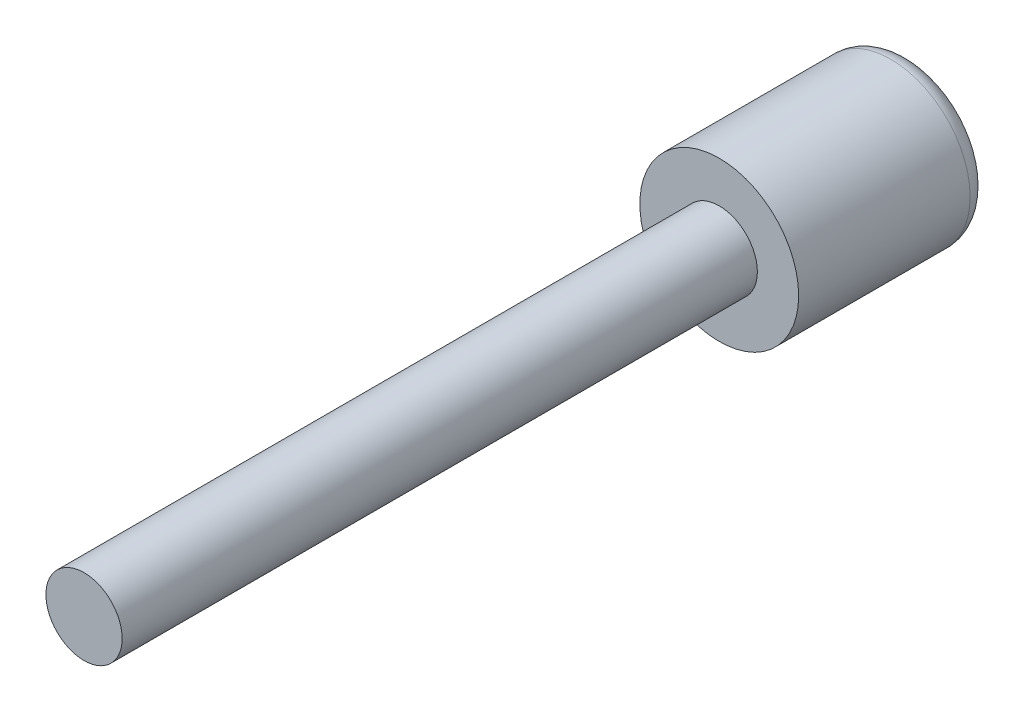
SolidWorks part; units mm, degrees
ref_plane "Front Plane" through (0, 0, 0) normal (0, 0, 1) x (1, 0, 0)
ref_plane "Top Plane" through (0, 0, 0) normal (0, 1, 0) x (1, 0, 0)
ref_plane "Right Plane" through (0, 0, 0) normal (1, 0, 0) x (0, 0, -1)
sketch "Sketch1" plane through (0, 0, 0) normal (0, 0, 1) x (1, 0, 0)
  circle A0 centre (0, 0) radius 1.25
  dimension "D1" = 2.5
extrude "Boss-Extrude1" add sketch "Sketch1" along normal blind 3
sketch "Sketch2" plane through (0, 0, 3) normal (0, 0, 1) x (1, 0, 0)
  circle A0 centre (0, 0) radius 0.6
  dimension "D1" = 1.2
extrude "Boss-Extrude2" add sketch "Sketch2" along normal blind 10
fillet "Fillet2" radius 0.3 1 edges at (1.25, 0, 0)
